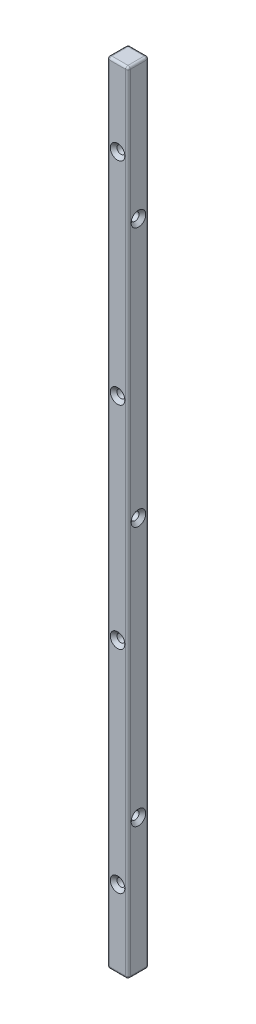
SolidWorks part; units mm, degrees
material "6061 Alloy"
ref_plane "Front Plane" through (0, 0, 0) normal (0, 0, 1) x (1, 0, 0)
ref_plane "Top Plane" through (0, 0, 0) normal (0, 1, 0) x (1, 0, 0)
ref_plane "Right Plane" through (0, 0, 0) normal (1, 0, 0) x (0, 0, -1)
sketch "Sketch2" plane through (0, 0, 0) normal (0, 1, 0) x (1, 0, 0)
  line L1 (-4.5, -4.5) -> (4.5, -4.5)
  line L2 (-4.5, -4.5) -> (-4.5, 4.5)
  line L3 (-4.5, 4.5) -> (4.5, 4.5)
  line L4 (4.5, -4.5) -> (4.5, 4.5)
  line L5 (-4.5, -4.5) -> (4.5, 4.5) construction
  line L6 (-4.5, 4.5) -> (4.5, -4.5) construction
  point P0 (0, 0)
extrude "Rail" add sketch "Sketch2" along normal blind 340.5
fillet "Rounded Edges" radius 1 12 edges at (4.5, 170.25, -4.5) (-4.5, 170.25, -4.5) (-4.5, 170.25, 4.5) (4.5, 170.25, 4.5) (0, 340.5, 4.5) (-4.5, 340.5, 0) (0, 340.5, -4.5) (4.5, 340.5, 0) (0, 0, 4.5) (-4.5, 0, 0) (0, 0, -4.5) (4.5, 0, 0)
hole_wizard "CSK for M3 Flat Head Machine Screw1" positions "3DSketch1" profile "Sketch9" countersink size "M3" standard "Ansi Metric" end condition through all
sketch3d "3DSketch1"
  line L1 (4.5, 1, 0) -> (4.5, 58.5, 0) construction
  line L2 (4.5, 1, 3.5) -> (4.5, 1, -3.5) construction
  line L3 (4.5, 58.5, 0) -> (4.5, 170.25, 0) construction
  line L4 (4.5, 170.25, 0) -> (4.5, 282, 0) construction
  line L5 (4.5, 282, 0) -> (4.5, 339.5, 0) construction
  line L6 (4.5, 339.5, -3.5) -> (4.5, 339.5, 3.5) construction
  line L8 (0, 1, 4.5) -> (0, 33.5, 4.5) construction
  line L9 (-3.5, 1, 4.5) -> (3.5, 1, 4.5) construction
  line L10 (0, 33.5, 4.5) -> (0, 124.6667, 4.5) construction
  line L11 (0, 124.6667, 4.5) -> (0, 215.8333, 4.5) construction
  line L12 (0, 215.8333, 4.5) -> (0, 307, 4.5) construction
  line L13 (0, 307, 4.5) -> (0, 339.5, 4.5) construction
  line L14 (3.5, 339.5, 4.5) -> (-3.5, 339.5, 4.5) construction
  point P0 (4.5, 58.5, 0)
  point P2 (4.5, 170.25, 0)
  point P8 (4.5, 282, 0)
  point P12 (0, 307, 4.5)
  point P14 (0, 215.8333, 4.5)
  point P16 (0, 124.6667, 4.5)
  point P18 (0, 33.5, 4.5)
  dimension "D1" = 58.5
  dimension "D2" = 33.5
sketch "Sketch9" plane through (4.5, 58.5, 0) normal (0, 1, 0) x (0, 0, -1)
  line L0 (0, 0) -> (0, 9)
  line L1 (0, 9) -> (1.7, 9)
  line L2 (1.7, 9) -> (1.7, 1.45)
  line L3 (1.7, 1.45) -> (3.15, 0)
  line L5 (3.15, 0) -> (0, 0)
  line L6 (-1.7, 1.45) -> (-3.15, 0) construction
  line L11 (0, -6.35) -> (0, 107.95) construction
  dimension "Thru Hole Dia." = 3.4
  dimension "Thru Hole Depth" = 9
  dimension "Near C'Sink Dia." = 6.3
  dimension "Near C'Sink Angle" = 90
